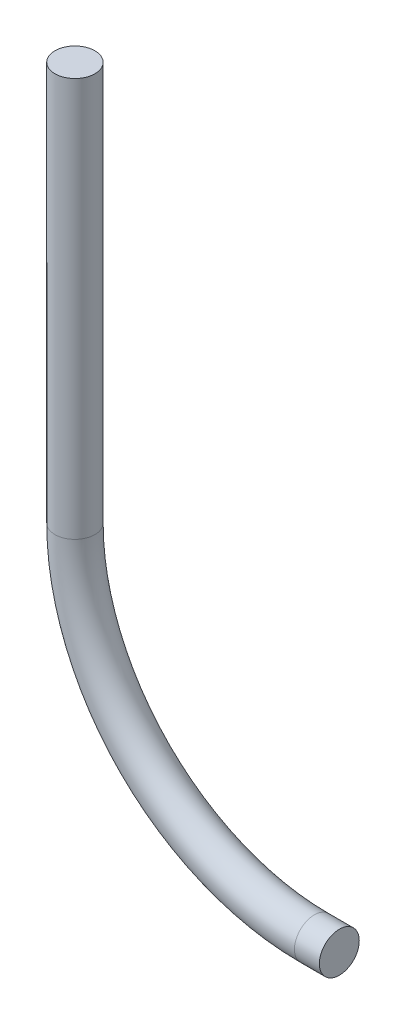
SolidWorks part; units mm, degrees
ref_plane "Front Plane" through (0, 0, 0) normal (0, 0, 1) x (1, 0, 0)
ref_plane "Top Plane" through (0, 0, 0) normal (0, 1, 0) x (1, 0, 0)
ref_plane "Right Plane" through (0, 0, 0) normal (1, 0, 0) x (0, 0, -1)
sketch "Sketch1" plane through (0, 0, 0) normal (0, 0, 1) x (1, 0, 0)
  line L0 (0, 0) -> (-5, 0)
  line L1 (-53, 48) -> (-53, 128)
  arc A0 (-5, 0) -> (-53, 48) centre (-5, 48) cw
  dimension "D1" = 48
  dimension "D2" = 5
  dimension "D3" = 80
sketch "Sketch2" plane through (0, 0, 0) normal (1, 0, 0) x (0, 0, -1)
  circle A0 centre (0, 0) radius 4
  dimension "D1" = 8
sweep "Sweep1" add profiles "Sketch2" path "Sketch1"
